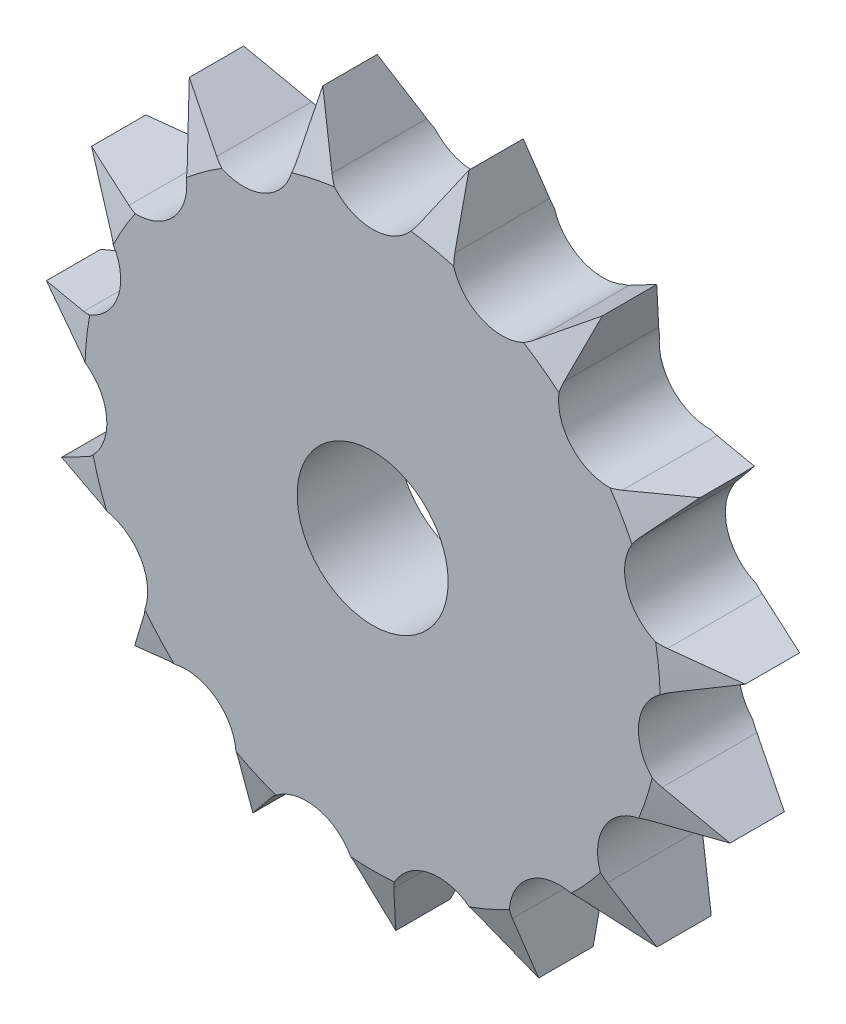
SolidWorks part; units mm, degrees
material "Sade Karbon Çeliği"
ref_plane "Ön Düzlem" through (0, 0, 0) normal (0, 0, 1) x (1, 0, 0)
ref_plane "Üst Düzlem" through (0, 0, 0) normal (0, 1, 0) x (1, 0, 0)
ref_plane "Sağ Düzlem" through (0, 0, 0) normal (1, 0, 0) x (0, 0, -1)
sketch "Çizim1" plane through (0, 0, 0) normal (0, 0, 1) x (1, 0, 0)
  circle A0 centre (0, 0) radius 35
  dimension "D1" = 70
extrude "Yükseklik-Ekstrüzyon1" add sketch "Çizim1" against normal blind 10
sketch "Çizim2" plane through (0, 0, 0) normal (0, 0, 1) x (1, 0, 0)
  line L0 (-12.8707, 31.5617) -> (17.31, 31.5617) construction
  line L1 (-4.3301, 29.0617) -> (-9.0087, 37.1653)
  line L2 (0, 35) -> (0, 28.1235) construction
  line L3 (4.3301, 29.0617) -> (9.0087, 37.1653)
  line L4 (-9.0087, 37.1653) -> (9.0087, 37.1653)
  circle A0 centre (0, 0) radius 35 construction
  arc A1 (-4.3301, 29.0617) -> (4.3301, 29.0617) centre (0, 31.5617) ccw
  dimension "D1" = 70
  dimension "D2" = 10
  dimension "D3" = 60
extrude "Kes-Ekstrüzyon1" cut sketch "Çizim2" against normal blind 10 contours L3 L4 L1 A1
sketch "Çizim5" plane through (0, 0, 0) normal (1, 0, 0) x (0, 0, -1)
  line L0 (-2.8362, 0) -> (11.532, 0) construction
pattern_circular "Dairesel Kaplama1" count 15 every 24 about axis through (0, 0, 0) along (0, 0, 1) of "Kes-Ekstrüzyon1"
sketch "Çizim6" plane through (0, 0, 0) normal (0, 0, 1) x (1, 0, 0)
  arc A0 (-4.3301, 29.0617) -> (4.3301, 29.0617) centre (0, 31.5617) ccw construction
  point P0 (0, 26.5617)
sketch "Çizim8" plane through (0, 0, 0) normal (0, 0, 1) x (1, 0, 0)
  circle A0 centre (0, 0) radius 7.5
  dimension "D1" = 15
extrude "Kes-Ekstrüzyon2" cut sketch "Çizim8" against normal blind 10
sketch "Çizim11" plane through (0, 0, 0) normal (1, 0, 0) x (0, 0, -1)
  line L0 (0, 26.5617) -> (10, 26.5617) construction
  line L1 (0, 26.5617) -> (0, 37.6409) construction
  line L2 (0, 28.5617) -> (2.9118, 36.5617)
  line L3 (0, 28.5617) -> (0, 36.5617)
  line L4 (0, 36.5617) -> (2.9118, 36.5617)
  line L5 (0, 26.5617) -> (0, 28.5617) construction
  line L6 (5, 26.5617) -> (5, 39.6423) construction
  line L7 (10, 36.5617) -> (7.0882, 36.5617)
  line L8 (10, 28.5617) -> (10, 36.5617)
  line L9 (10, 28.5617) -> (7.0882, 36.5617)
  dimension "D1" = 2
revolve "Kes-Döndür1" cut sketch "Çizim11" angle 360 about L0
